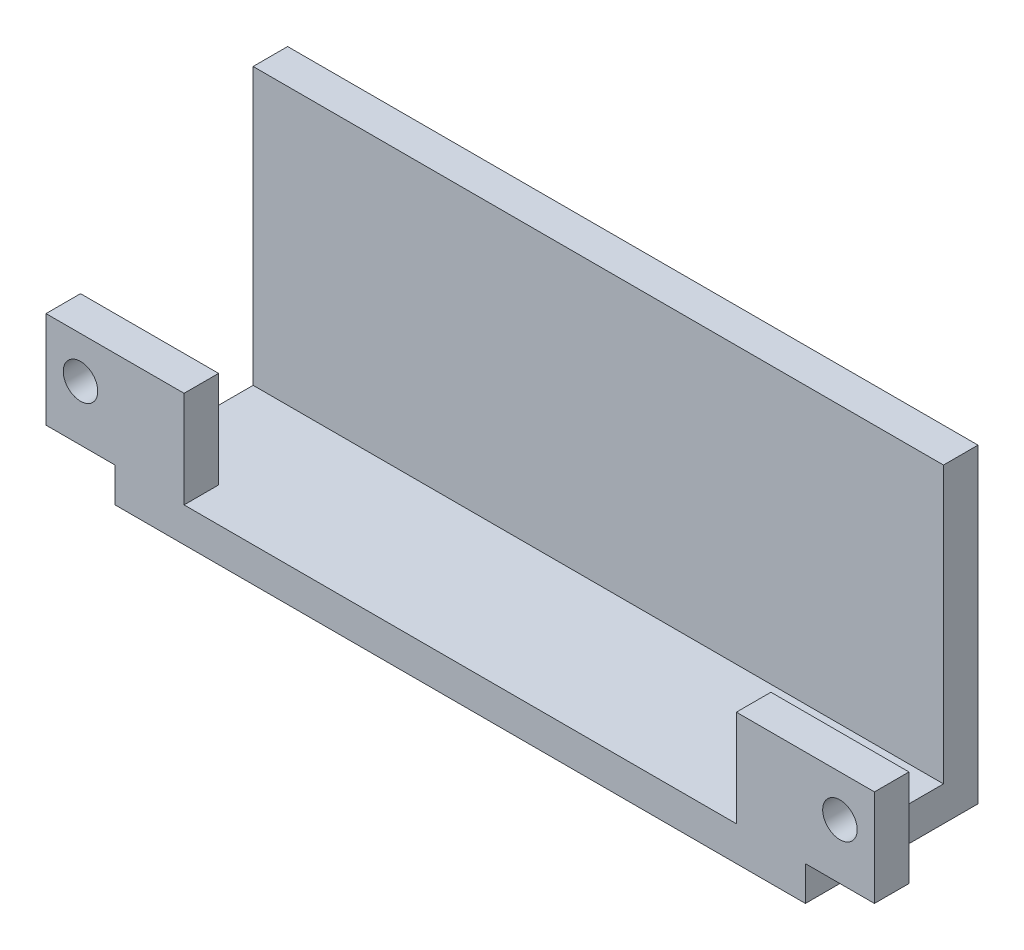
SolidWorks part; units mm, degrees
ref_plane "Front Plane" through (0, 0, 0) normal (0, 0, 1) x (1, 0, 0)
ref_plane "Top Plane" through (0, 0, 0) normal (0, 1, 0) x (1, 0, 0)
ref_plane "Right Plane" through (0, 0, 0) normal (1, 0, 0) x (0, 0, -1)
sketch "Sketch1" plane through (0, 0, 0) normal (0, 1, 0) x (1, 0, 0)
  line L1 (-63.5, 15.875) -> (63.5, 15.875)
  line L2 (-63.5, 15.875) -> (-63.5, -15.875)
  line L3 (-63.5, -15.875) -> (63.5, -15.875)
  line L4 (63.5, 15.875) -> (63.5, -15.875)
  line L5 (-63.5, 15.875) -> (63.5, -15.875) construction
  line L6 (-63.5, -15.875) -> (63.5, 15.875) construction
  point P0 (0, 0)
  dimension "D1" = 127
  dimension "D2" = 31.75
extrude "Boss-Extrude1" add sketch "Sketch1" along normal blind 6.35
sketch "Sketch2" plane through (0, 6.35, 0) normal (0, 1, 0) x (1, 0, 0)
  line L5 (-63.5, -15.875) -> (63.5, -15.875) construction
  line L6 (-50.8, -15.875) -> (-76.2, -15.875)
  line L7 (-50.8, -15.875) -> (-50.8, -9.525)
  line L8 (-50.8, -9.525) -> (-76.2, -9.525)
  line L9 (-76.2, -15.875) -> (-76.2, -9.525)
  line L10 (-63.5, 15.875) -> (-63.5, -15.875) construction
  line L11 (50.8, -15.875) -> (76.2, -15.875)
  line L12 (50.8, -15.875) -> (50.8, -9.525)
  line L13 (50.8, -9.525) -> (76.2, -9.525)
  line L14 (76.2, -15.875) -> (76.2, -9.525)
  line L15 (63.5, -15.875) -> (63.5, 15.875) construction
  dimension "D1" = 6.35
  dimension "D2" = 12.7
  dimension "D3" = 25.4
  dimension "D4" = 12.7
extrude "Boss-Extrude2" add sketch "Sketch2" along normal blind 17.78
sketch "Sketch3" plane through (0, 0, 9.525) normal (0, 0, -1) x (-1, 0, 0)
  line L4 (76.2, 24.13) -> (76.2, 6.35) construction
  line L5 (-76.2, 24.13) -> (-76.2, 6.35) construction
  line L6 (-76.2, 24.13) -> (-50.8, 24.13) construction
  circle A0 centre (69.85, 16.51) radius 3.175
  circle A1 centre (-69.85, 16.51) radius 3.175
  dimension "D1" = 6.35
  dimension "D2" = 6.35
  dimension "D3" = 6.35
  dimension "D4" = 7.62
extrude "Cut-Extrude1" cut sketch "Sketch3" against normal up to surface (6.35 mm away) up to face at (0, 11.2183, 15.875)
sketch "Sketch4" plane through (0, 6.35, 0) normal (0, 1, 0) x (1, 0, 0)
  line L0 (63.5, -9.525) -> (63.5, 15.875) construction
  line L1 (-63.5, 15.875) -> (63.5, 15.875)
  line L2 (-63.5, 15.875) -> (-63.5, 9.525)
  line L3 (-63.5, 9.525) -> (63.5, 9.525)
  line L4 (63.5, 15.875) -> (63.5, 9.525)
  dimension "D1" = 6.35
extrude "Boss-Extrude3" add sketch "Sketch4" along normal blind 50.8
